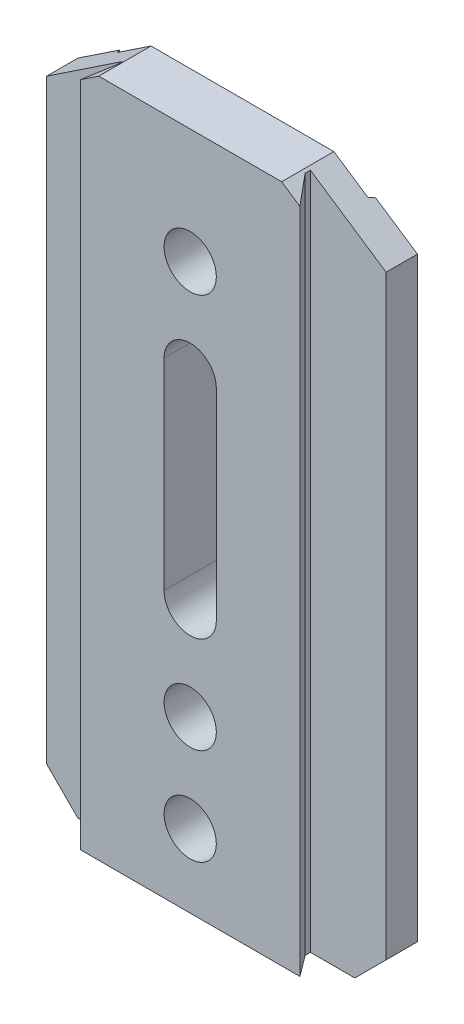
SolidWorks part; units mm, degrees
ref_plane "Front Plane" through (0, 0, 0) normal (0, 0, 1) x (1, 0, 0)
ref_plane "Top Plane" through (0, 0, 0) normal (0, 1, 0) x (1, 0, 0)
ref_plane "Right Plane" through (0, 0, 0) normal (1, 0, 0) x (0, 0, -1)
sketch "Sketch1" plane through (0, 0, 0) normal (0, 0, 1) x (1, 0, 0)
  line L1 (-32.5, 65) -> (32.5, 65)
  line L2 (-32.5, 65) -> (-32.5, -65)
  line L3 (-32.5, -65) -> (32.5, -65)
  line L4 (32.5, 65) -> (32.5, -65)
  dimension "D1" = 65
  dimension "D2" = 130
  dimension "D3" = 65
  dimension "D4" = 32.5
extrude "Main Body Extrude" add sketch "Sketch1" along normal blind 11
sketch "Sketch2" plane through (0, 0, 11) normal (0, 0, 1) x (1, 0, 0)
  line L0 (32.5, 65) -> (-32.5, 65) construction
  line L1 (-32.5, 65) -> (-32.5, -65) construction
  line L2 (32.5, -65) -> (32.5, 65) construction
  line L3 (-32.5, 55) -> (-17.5, 65)
  line L4 (-17.5, 65) -> (-32.5, 65)
  line L5 (-32.5, 65) -> (-32.5, 55)
  line L6 (17.5, 65) -> (32.5, 55)
  line L7 (32.5, 55) -> (32.5, 65)
  line L8 (32.5, 65) -> (17.5, 65)
  point P0 (0, 65)
  point P1 (-17.5, 65)
  point P4 (17.5, 65)
  point P6 (-32.5, 55)
  point P7 (32.5, 55)
  dimension "D1" = 17.5
  dimension "D2" = 17.5
  dimension "D3" = 10
  dimension "D4" = 10
sketch "Sketch3" plane through (0, 0, 11) normal (0, 0, 1) x (1, 0, 0)
  line L0 (-32.5, -65) -> (32.5, -65) construction
  line L1 (-32.5, 65) -> (-32.5, -65) construction
  line L2 (32.5, -65) -> (32.5, 65) construction
  line L3 (-26.5, -65) -> (-32.5, -59)
  line L4 (-32.5, -59) -> (-32.5, -65)
  line L5 (-32.5, -65) -> (-26.5, -65)
  line L6 (26.5, -65) -> (32.5, -59)
  line L7 (32.5, -59) -> (32.5, -65)
  line L8 (32.5, -65) -> (26.5, -65)
  point P0 (-26.5, -65)
  point P1 (26.5, -65)
  point P4 (-32.5, -59)
  point P7 (32.5, -59)
  dimension "D1" = 6
  dimension "D2" = 6
  dimension "D3" = 6
  dimension "D4" = 6
sketch "Sketch4" plane through (0, 0, 11) normal (0, 0, 1) x (1, 0, 0)
  line L0 (-32.5, -65) -> (32.5, -65) construction
  line L1 (32.5, 65) -> (-32.5, 65) construction
  line L4 (-5, -14) -> (-5, 24.5)
  line L6 (5, -14) -> (5, 24.5)
  circle A0 centre (0, -51) radius 5
  circle A1 centre (0, -32.5) radius 5
  circle A2 centre (0, 43) radius 5
  arc A3 (5, 24.5) -> (-5, 24.5) centre (0, 24.5) ccw
  arc A4 (-5, -14) -> (5, -14) centre (0, -14) ccw
  dimension "D1" = 14
  dimension "D2" = 18.5
  dimension "D3" = 22
  dimension "D4" = 18.5
  dimension "D5" = 18.5
extrude "Bolt Holes" cut sketch "Sketch4" against normal blind 11
sketch "Sketch6" plane through (0, 65, 0) normal (0, 1, 0) x (1, 0, 0)
  line L0 (32.5, -11) -> (-32.5, -11) construction
  line L1 (21, -11) -> (18, -7)
  line L2 (18, -7) -> (18, -6)
  line L3 (18, -6) -> (32.5, -6)
  line L4 (32.5, -11) -> (32.5, 0) construction
  line L5 (32.5, -6) -> (32.5, -11)
  line L6 (32.5, -11) -> (21, -11)
  line L9 (-32.5, -11) -> (-21, -11)
  line L10 (-32.5, -6) -> (-32.5, -11)
  line L11 (-18, -6) -> (-32.5, -6)
  line L12 (-18, -7) -> (-18, -6)
  line L13 (-21, -11) -> (-18, -7)
  point P0 (21, -11)
  point P1 (18, -7)
  point P22 (-18, -7)
  point P23 (-21, -11)
  dimension "D1" = 21
  dimension "D2" = 4
  dimension "D3" = 3
extrude "Undercarriage Cut" cut sketch "Sketch6" against normal blind 135
extrude "Top Corner Cuts" cut sketch "Sketch2" against normal blind 11
extrude "Bottom Corner Cuts" cut sketch "Sketch3" against normal blind 11
sketch "Sketch7" plane through (0, -65, 0) normal (0, -1, 0) x (-1, 0, 0)
  line L0 (24.5, 0) -> (-24.5, 0)
  line L1 (26.5, 0) -> (-26.5, 0) construction
  line L2 (-24.5, 0) -> (-24, -1)
  line L3 (-24, -1) -> (24, -1)
  line L5 (24.5, 0) -> (24, -1)
  point P4 (-24, -1)
  dimension "D1" = 8
  dimension "D2" = 8
  dimension "D3" = 0.5
  dimension "D4" = 1
extrude "Top Cut" cut sketch "Sketch7" against normal blind 130
